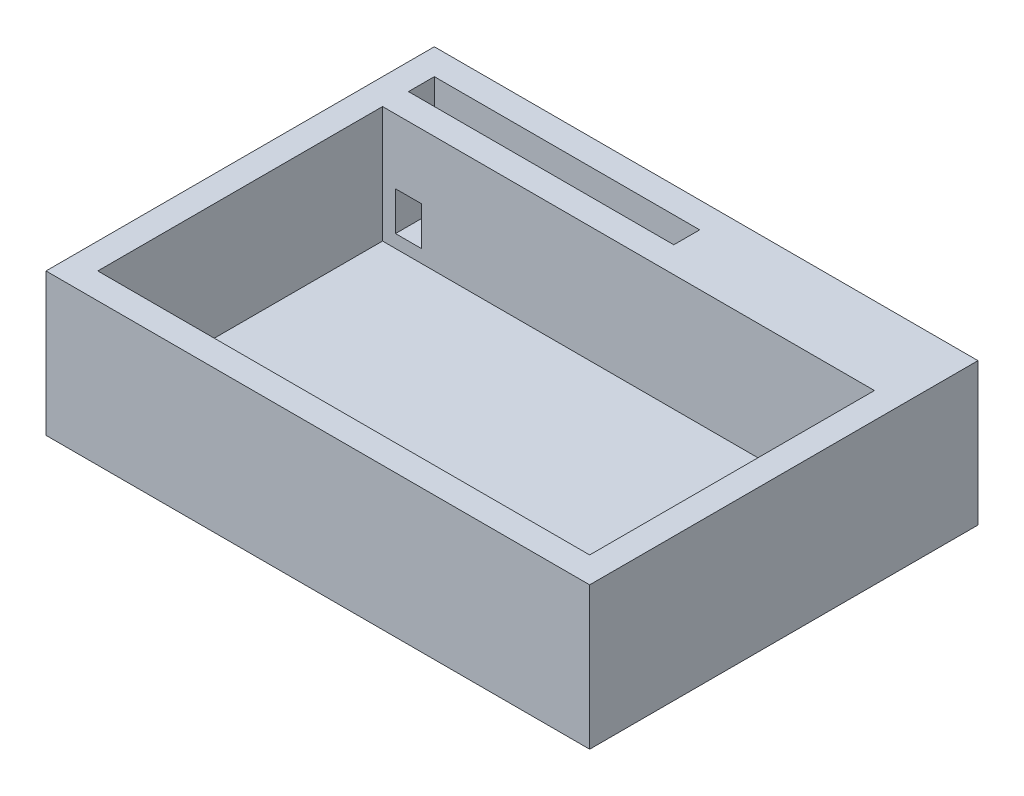
SolidWorks part; units mm, degrees
ref_plane "Front Plane" through (0, 0, 0) normal (0, 0, 1) x (1, 0, 0)
ref_plane "Top Plane" through (0, 0, 0) normal (0, 1, 0) x (1, 0, 0)
ref_plane "Right Plane" through (0, 0, 0) normal (1, 0, 0) x (0, 0, -1)
sketch "Sketch1" plane through (0, 0, 0) normal (0, 1, 0) x (1, 0, 0)
  line L1 (0, 0) -> (42, 0)
  line L2 (0, 0) -> (0, 30)
  line L3 (0, 30) -> (42, 30)
  line L4 (42, 0) -> (42, 30)
  dimension "D1" = 30
  dimension "D2" = 42
extrude "Boss-Extrude1" add sketch "Sketch1" along normal blind 2
sketch "Sketch2" plane through (0, 2, 0) normal (0, 1, 0) x (1, 0, 0)
  line L0 (22.5, 26) -> (22.5, 28)
  line L1 (0, 30) -> (42, 30)
  line L2 (0, 30) -> (0, 0)
  line L3 (0, 0) -> (42, 0)
  line L4 (42, 30) -> (42, 0)
  line L5 (2, 28) -> (22.5, 28)
  line L6 (2, 28) -> (2, 26)
  line L7 (2, 2) -> (40, 2)
  line L8 (40, 24) -> (40, 2)
  line L9 (2, 26) -> (22.5, 26)
  line L11 (2, 24) -> (40, 24)
  line L13 (2, 24) -> (2, 2)
  point P9 (0, 0)
  point P13 (0, 0)
  dimension "D1" = 2
  dimension "D2" = 2
  dimension "D3" = 2
  dimension "D4" = 2
  dimension "D5" = 2
  dimension "D6" = 2
  dimension "D7" = 20.5
extrude "Boss-Extrude2" add sketch "Sketch2" along normal blind 9
sketch "Sketch6" plane through (0, 0, -24) normal (0, 0, 1) x (1, 0, 0)
  line L0 (40, 2) -> (2, 2) construction
  line L5 (3, 3) -> (5, 3)
  line L6 (3, 3) -> (3, 6)
  line L7 (3, 6) -> (5, 6)
  line L8 (5, 3) -> (5, 6)
  line L9 (2, 11) -> (2, 2) construction
  dimension "D1" = 3
  dimension "D2" = 2
  dimension "D3" = 1
  dimension "D4" = 1
extrude "Cut-Extrude2" cut sketch "Sketch6" against normal blind 2
